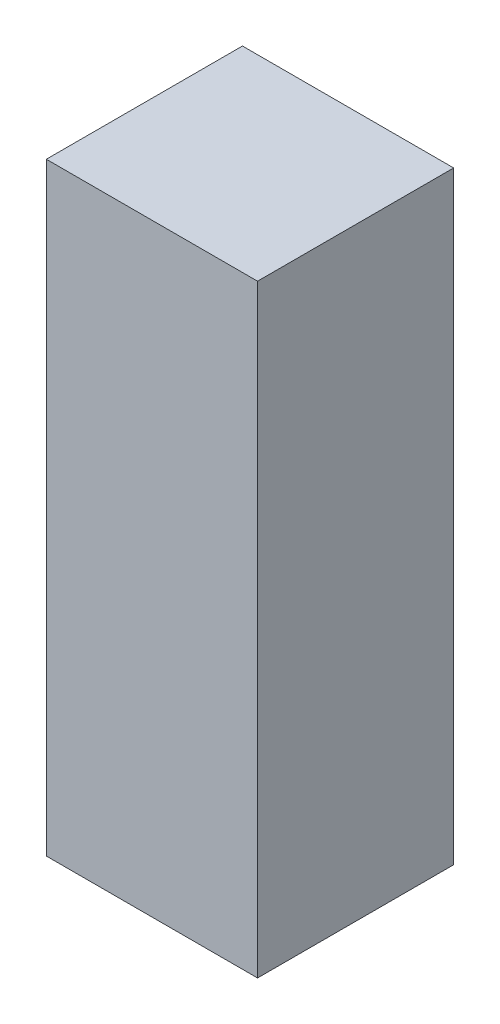
SolidWorks part; units mm, degrees
ref_plane "Front Plane" through (0, 0, 0) normal (0, 0, 1) x (1, 0, 0)
ref_plane "Top Plane" through (0, 0, 0) normal (0, 1, 0) x (1, 0, 0)
ref_plane "Right Plane" through (0, 0, 0) normal (1, 0, 0) x (0, 0, -1)
other "Configuration Table"
sketch "Sketch1" plane through (0, 0, 0) normal (0, 0, 1) x (1, 0, 0)
  line L1 (24, 1720) -> (38, 1720)
  line L2 (24, 1720) -> (24, 1760)
  line L3 (24, 1760) -> (38, 1760)
  line L4 (38, 1720) -> (38, 1760)
extrude "OVEN_fan_filtre_kapagi_mentese_1_1" add sketch "Sketch1" along normal blind 13 from offset 20 separate body
